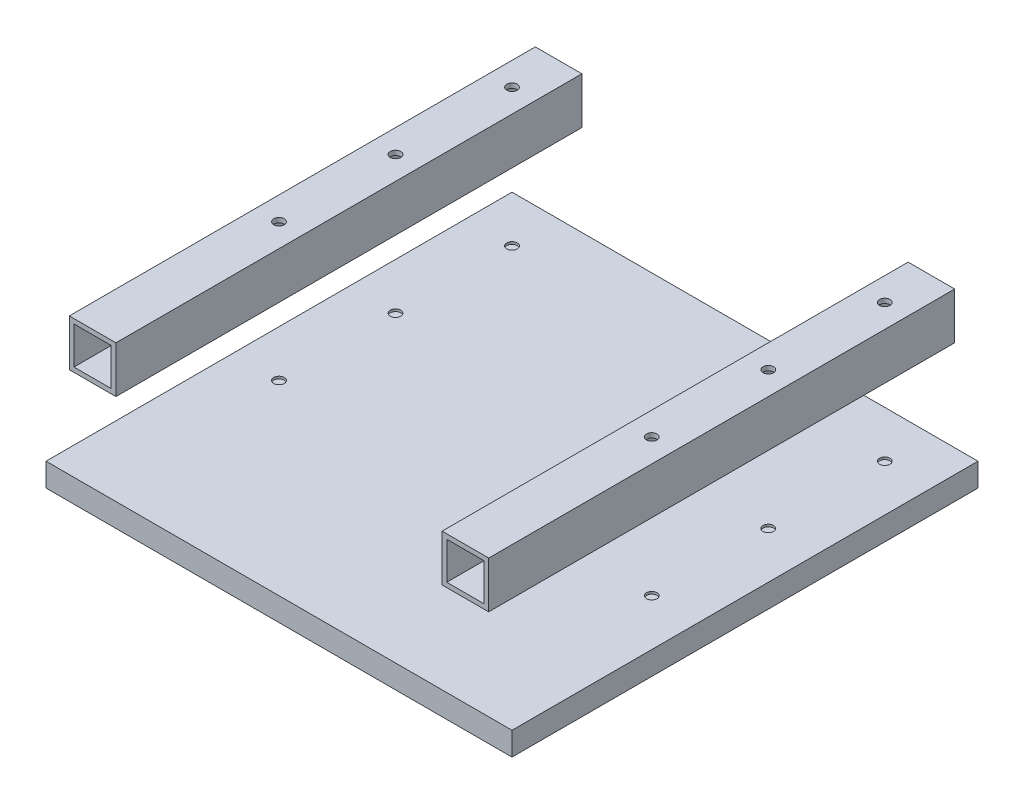
SolidWorks part; units mm, degrees
ref_plane "前视基准面" through (0, 0, 0) normal (0, 0, 1) x (1, 0, 0)
ref_plane "上视基准面" through (0, 0, 0) normal (0, 1, 0) x (1, 0, 0)
ref_plane "右视基准面" through (0, 0, 0) normal (1, 0, 0) x (0, 0, -1)
sketch "草图1" plane through (0, 0, 0) normal (0, 0, 1) x (1, 0, 0)
  line L0 (0, -998.8437) -> (0, 49001.1563) construction
  line L1 (-100, -39) -> (100, -39)
  line L2 (-100, -39) -> (-100, -49)
  line L3 (-100, -49) -> (100, -49)
  line L4 (100, -39) -> (100, -49)
  line L5 (-100, -39) -> (100, -49) construction
  line L6 (-100, -49) -> (100, -39) construction
  line L7 (-90, 20) -> (-70, 20)
  line L8 (-90, 20) -> (-90, 0)
  line L9 (-90, 0) -> (-70, 0)
  line L10 (-70, 20) -> (-70, 0)
  line L11 (-90, 20) -> (-70, 0) construction
  line L12 (-90, 0) -> (-70, 20) construction
  line L13 (90, 0) -> (70, 0)
  line L14 (-88, 18) -> (-72, 18)
  line L15 (-88, 18) -> (-88, 2)
  line L16 (-88, 2) -> (-72, 2)
  line L17 (-72, 18) -> (-72, 2)
  line L18 (-88, 18) -> (-72, 2) construction
  line L19 (-88, 2) -> (-72, 18) construction
  line L20 (70, 20) -> (70, 0)
  line L21 (90, 20) -> (70, 20)
  line L22 (90, 20) -> (90, 0)
  line L23 (88, 2) -> (72, 2)
  line L24 (72, 18) -> (72, 2)
  line L25 (88, 18) -> (72, 18)
  line L26 (88, 18) -> (88, 2)
  line L27 (88, 2) -> (72, 18) construction
  line L28 (88, 18) -> (72, 2) construction
  point P0 (0, -44)
  point P5 (-80, 10)
  point P13 (-80, 10)
  point P26 (80, 10)
  dimension "D1" = 10
  dimension "D2" = 200
  dimension "D3" = 20
  dimension "D4" = 59
  dimension "D5" = 70
  dimension "D6" = 16
extrude "凸台-拉伸1" add sketch "草图1" along normal mid plane 200
sketch "草图2" plane through (0, 20, 0) normal (0, 1, 0) x (1, 0, 0)
  circle A0 centre (80, 80) radius 2.25 construction
  circle A1 centre (80, 30) radius 2.25 construction
  circle A2 centre (80, -20) radius 2.25 construction
  circle A3 centre (-80, -20) radius 2.25 construction
  circle A4 centre (-80, 30) radius 2.25 construction
  circle A5 centre (-80, 80) radius 2.25 construction
  circle A6 centre (80, 80) radius 2.25
  circle A7 centre (80, 30) radius 2.25
  circle A8 centre (80, -20) radius 2.25
  circle A9 centre (-80, -20) radius 2.25
  circle A10 centre (-80, 30) radius 2.25
  circle A11 centre (-80, 80) radius 2.25
extrude "切除-拉伸1" cut sketch "草图2" against normal blind 20
sketch "草图3" plane through (0, 20, 0) normal (0, 1, 0) x (1, 0, 0)
  circle A0 centre (80, -20) radius 2.25 construction
  circle A1 centre (80, 30) radius 2.25 construction
  circle A2 centre (80, 80) radius 2.25 construction
  circle A3 centre (-80, -20) radius 2.25 construction
  circle A4 centre (-80, 30) radius 2.25 construction
  circle A5 centre (-80, 80) radius 2.25 construction
  circle A6 centre (80, -20) radius 2.25
  circle A7 centre (80, 30) radius 2.25
  circle A8 centre (80, 80) radius 2.25
  circle A9 centre (-80, -20) radius 2.25
  circle A10 centre (-80, 30) radius 2.25
  circle A11 centre (-80, 80) radius 2.25
extrude "切除-拉伸6" cut sketch "草图3" against normal blind 60
